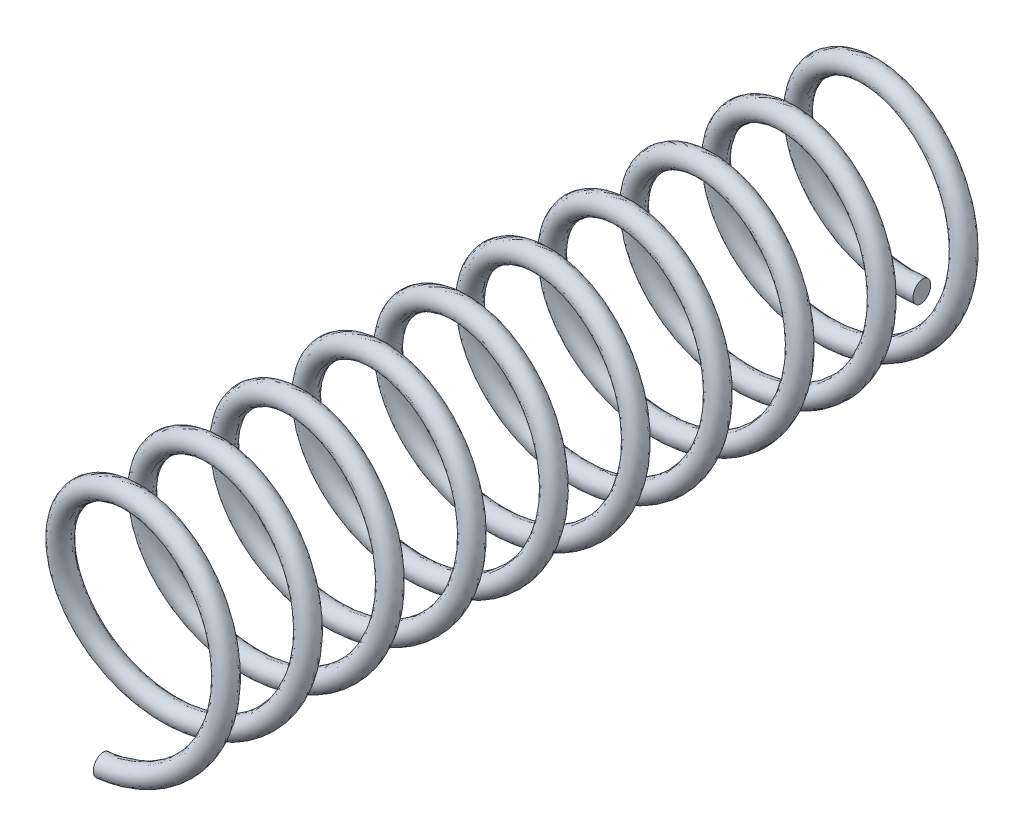
SolidWorks part; units mm, degrees
ref_plane "Front Plane" through (0, 0, 0) normal (0, 0, 1) x (1, 0, 0)
ref_plane "Top Plane" through (0, 0, 0) normal (0, 1, 0) x (1, 0, 0)
ref_plane "Right Plane" through (0, 0, 0) normal (1, 0, 0) x (0, 0, -1)
sketch "Sketch1" plane through (0, 0, 0) normal (0, 0, 1) x (1, 0, 0)
  circle A0 centre (0, 0) radius 25
  dimension "D1" = 50
curve "Helix/Spiral1" pitch 20 height 200 turns 10
sweep "Sweep4" add path "Helix/Spiral1" circular profile diameter 5 parameters "D3"=5
